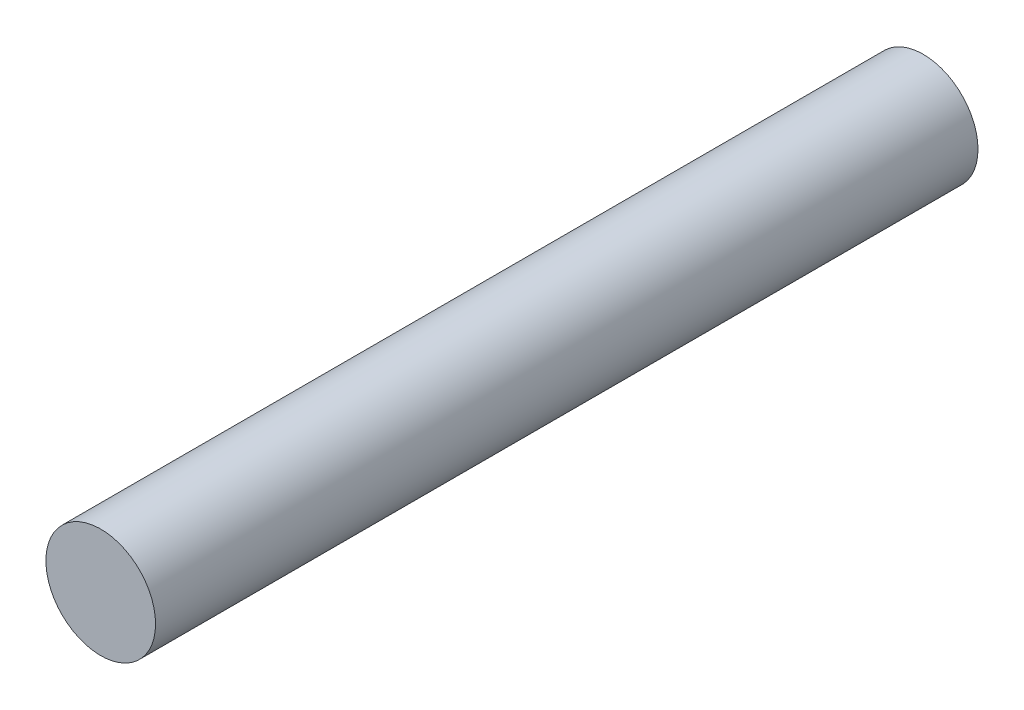
SolidWorks part; units mm, degrees
ref_plane "Płaszczyzna przednia" through (0, 0, 0) normal (0, 0, 1) x (1, 0, 0)
ref_plane "Płaszczyzna górna" through (0, 0, 0) normal (0, 1, 0) x (1, 0, 0)
ref_plane "Płaszczyzna prawa" through (0, 0, 0) normal (1, 0, 0) x (0, 0, -1)
sketch "Szkic1" plane through (0, 0, 0) normal (0, 0, 1) x (1, 0, 0)
  circle A0 centre (0, 0) radius 10
extrude "Dodanie-wyciągnięcie1" add sketch "Szkic1" along normal blind 150
